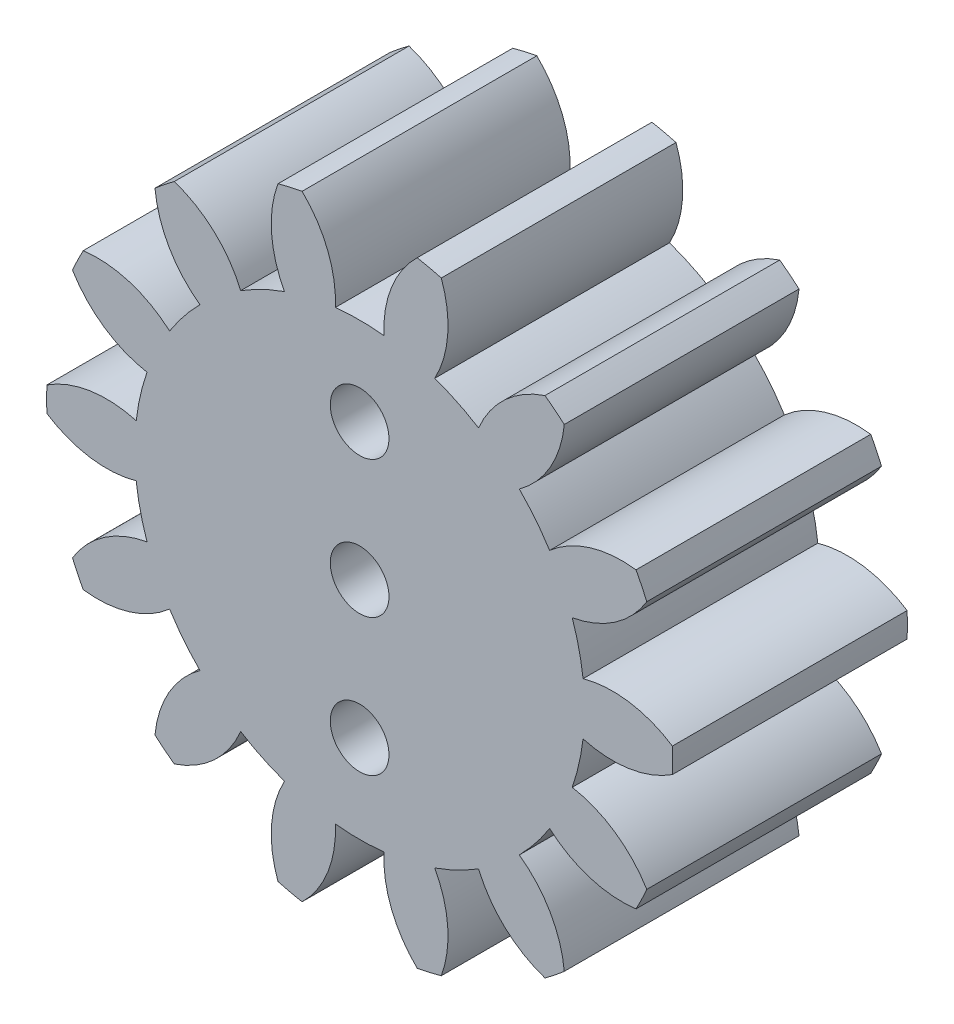
SolidWorks part; units mm, degrees
ref_plane "Alzado" through (0, 0, 0) normal (0, 0, 1) x (1, 0, 0)
ref_plane "Planta" through (0, 0, 0) normal (0, 1, 0) x (1, 0, 0)
ref_plane "Vista lateral" through (0, 0, 0) normal (1, 0, 0) x (0, 0, -1)
sketch "Croquis1" plane through (0, 0, 0) normal (0, 0, 1) x (1, 0, 0)
  circle A1 centre (0, 0) radius 1.5
  arc A112 (-14.1302, -7.5058) -> (-9.7127, -6.1555) centre (-13.4128, -1.9519) ccw
  arc A113 (-9.7127, -6.1555) -> (-8.1624, -8.0995) centre (0, 0) ccw
  arc A114 (-8.1624, -8.0995) -> (-10.4619, -12.1058) centre (-4.8876, -12.6421) ccw
  arc A115 (-10.4619, -12.1058) -> (-9.4743, -12.8934) centre (0, 0) ccw
  arc A116 (-9.4743, -12.8934) -> (-6.0801, -9.7601) centre (-11.2376, -7.5782) ccw
  arc A117 (-6.0801, -9.7601) -> (-3.8398, -10.8389) centre (0, 0) ccw
  arc A118 (-3.8398, -10.8389) -> (-4.1733, -15.4461) centre (1.0816, -13.5108) ccw
  arc A119 (-4.1733, -15.4461) -> (-2.9418, -15.7272) centre (0, 0) ccw
  arc A120 (-2.9418, -15.7272) -> (-1.2433, -11.4316) centre (-6.8366, -11.7035) ccw
  arc A121 (-1.2433, -11.4316) -> (1.2433, -11.4316) centre (0, 0) ccw
  arc A122 (1.2433, -11.4316) -> (2.9418, -15.7272) centre (6.8366, -11.7035) ccw
  arc A123 (2.9418, -15.7272) -> (4.1733, -15.4461) centre (0, 0) ccw
  arc A124 (4.1733, -15.4461) -> (3.8398, -10.8389) centre (-1.0816, -13.5108) ccw
  arc A125 (3.8398, -10.8389) -> (6.0801, -9.7601) centre (0, 0) ccw
  arc A126 (6.0801, -9.7601) -> (9.4743, -12.8934) centre (11.2376, -7.5782) ccw
  arc A127 (9.4743, -12.8934) -> (10.4619, -12.1058) centre (0, 0) ccw
  arc A128 (10.4619, -12.1058) -> (8.1624, -8.0995) centre (4.8876, -12.6421) ccw
  arc A129 (8.1624, -8.0995) -> (9.7127, -6.1555) centre (0, 0) ccw
  arc A130 (9.7127, -6.1555) -> (14.1302, -7.5058) centre (13.4128, -1.9519) ccw
  arc A131 (14.1302, -7.5058) -> (14.6783, -6.3677) centre (0, 0) ccw
  arc A132 (14.6783, -6.3677) -> (10.8683, -3.7559) centre (9.8888, -9.2695) ccw
  arc A133 (10.8683, -3.7559) -> (11.4216, -1.3317) centre (0, 0) ccw
  arc A134 (11.4216, -1.3317) -> (15.9875, -0.6316) centre (12.9314, 4.061) ccw
  arc A135 (15.9875, -0.6316) -> (15.9875, 0.6316) centre (0, 0) ccw
  arc A136 (15.9875, 0.6316) -> (11.4216, 1.3317) centre (12.9314, -4.061) ccw
  arc A137 (11.4216, 1.3317) -> (10.8683, 3.7559) centre (0, 0) ccw
  arc A138 (10.8683, 3.7559) -> (14.6783, 6.3677) centre (9.8888, 9.2695) ccw
  arc A139 (14.6783, 6.3677) -> (14.1302, 7.5058) centre (0, 0) ccw
  arc A140 (14.1302, 7.5058) -> (9.7127, 6.1555) centre (13.4128, 1.9519) ccw
  arc A141 (9.7127, 6.1555) -> (8.1624, 8.0995) centre (0, 0) ccw
  arc A142 (8.1624, 8.0995) -> (10.4619, 12.1058) centre (4.8876, 12.6421) ccw
  arc A143 (10.4619, 12.1058) -> (9.4743, 12.8934) centre (0, 0) ccw
  arc A144 (9.4743, 12.8934) -> (6.0801, 9.7601) centre (11.2376, 7.5782) ccw
  arc A145 (6.0801, 9.7601) -> (3.8398, 10.8389) centre (0, 0) ccw
  arc A146 (3.8398, 10.8389) -> (4.1733, 15.4461) centre (-1.0816, 13.5108) ccw
  arc A147 (4.1733, 15.4461) -> (2.9418, 15.7272) centre (0, 0) ccw
  arc A148 (2.9418, 15.7272) -> (1.2433, 11.4316) centre (6.8366, 11.7035) ccw
  arc A149 (1.2433, 11.4316) -> (-1.2433, 11.4316) centre (0, 0) ccw
  arc A150 (-1.2433, 11.4316) -> (-2.9418, 15.7272) centre (-6.8366, 11.7035) ccw
  arc A151 (-2.9418, 15.7272) -> (-4.1733, 15.4461) centre (0, 0) ccw
  arc A152 (-4.1733, 15.4461) -> (-3.8398, 10.8389) centre (1.0816, 13.5108) ccw
  arc A153 (-3.8398, 10.8389) -> (-6.0801, 9.7601) centre (0, 0) ccw
  arc A154 (-6.0801, 9.7601) -> (-9.4743, 12.8934) centre (-11.2376, 7.5782) ccw
  arc A155 (-9.4743, 12.8934) -> (-10.4619, 12.1058) centre (0, 0) ccw
  arc A156 (-10.4619, 12.1058) -> (-8.1624, 8.0995) centre (-4.8876, 12.6421) ccw
  arc A157 (-8.1624, 8.0995) -> (-9.7127, 6.1555) centre (0, 0) ccw
  arc A158 (-9.7127, 6.1555) -> (-14.1302, 7.5058) centre (-13.4128, 1.9519) ccw
  arc A159 (-14.1302, 7.5058) -> (-14.6783, 6.3677) centre (0, 0) ccw
  arc A160 (-14.6783, 6.3677) -> (-10.8683, 3.7559) centre (-9.8888, 9.2695) ccw
  arc A161 (-10.8683, 3.7559) -> (-11.4216, 1.3317) centre (0, 0) ccw
  arc A162 (-11.4216, 1.3317) -> (-15.9875, 0.6316) centre (-12.9314, -4.061) ccw
  arc A163 (-15.9875, 0.6316) -> (-15.9875, -0.6316) centre (0, 0) ccw
  arc A164 (-15.9875, -0.6316) -> (-11.4216, -1.3317) centre (-12.9314, 4.061) ccw
  arc A165 (-11.4216, -1.3317) -> (-10.8683, -3.7559) centre (0, 0) ccw
  arc A166 (-10.8683, -3.7559) -> (-14.6783, -6.3677) centre (-9.8888, -9.2695) ccw
  arc A167 (-14.6783, -6.3677) -> (-14.1302, -7.5058) centre (0, 0) ccw
extrude "Saliente-Extruir1" add sketch "Croquis1" along normal blind 12
sketch "Croquis2" plane through (0, 0, 0) normal (0, 0, -1) x (-1, 0, 0)
  line L0 (0, 0) -> (0, 7) construction
  circle A0 centre (0, 7) radius 1.5
  circle A1 centre (0, -7) radius 1.5
  point P8 (0, 0)
  dimension "D1" = 3
  dimension "D2" = 7
  dimension "D3" = 2
extrude "Cortar-Extruir1" cut sketch "Croquis2" against normal through all
